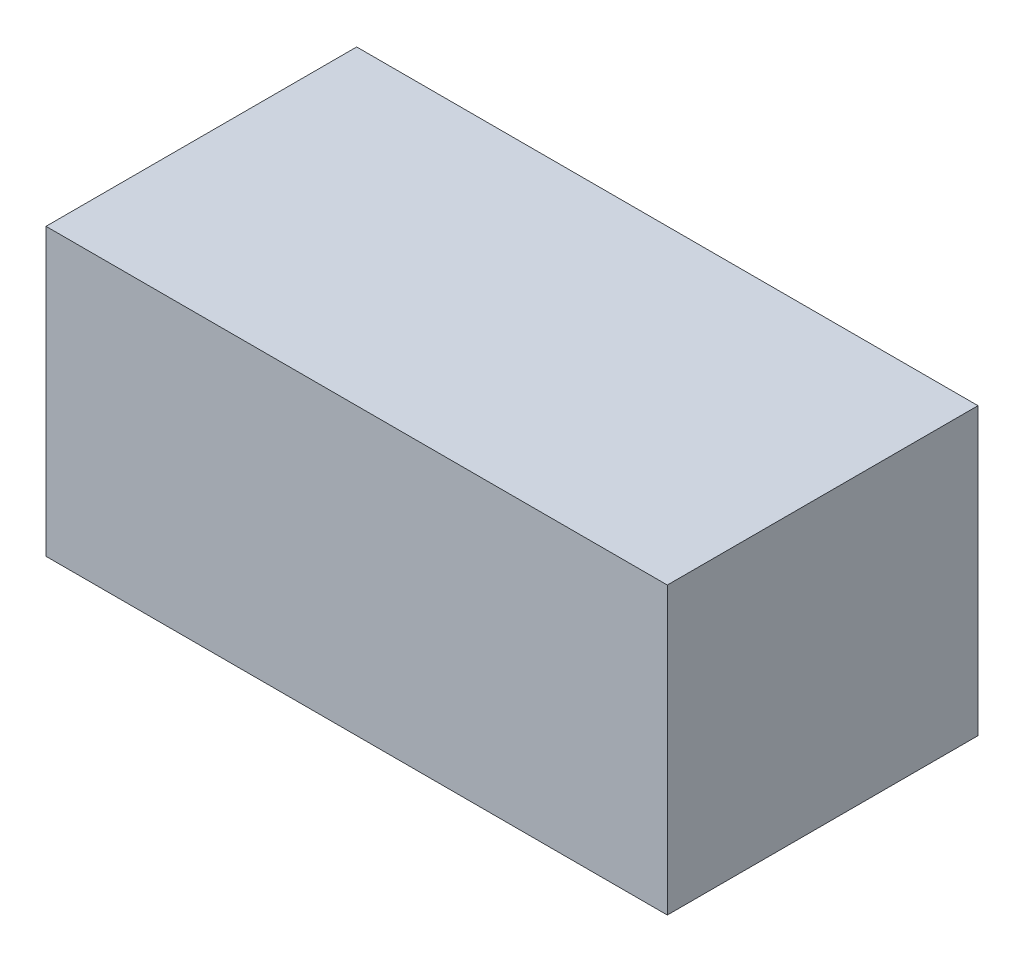
SolidWorks part; units mm, degrees
ref_plane "Plano frontal" through (0, 0, 0) normal (0, 0, 1) x (1, 0, 0)
ref_plane "Plano superior" through (0, 0, 0) normal (0, 1, 0) x (1, 0, 0)
ref_plane "Plano direito" through (0, 0, 0) normal (1, 0, 0) x (0, 0, -1)
sketch "Esboço1" plane through (0, 0, 0) normal (0, 1, 0) x (1, 0, 0)
  line L1 (-25, 12.5) -> (25, 12.5)
  line L2 (-25, 12.5) -> (-25, -12.5)
  line L3 (-25, -12.5) -> (25, -12.5)
  line L4 (25, 12.5) -> (25, -12.5)
  line L5 (-25, 12.5) -> (25, -12.5) construction
  line L6 (-25, -12.5) -> (25, 12.5) construction
  point P0 (0, 0)
  dimension "D1" = 25
  dimension "D2" = 50
extrude "Ressalto-extrusão1" add sketch "Esboço1" along normal blind 23
